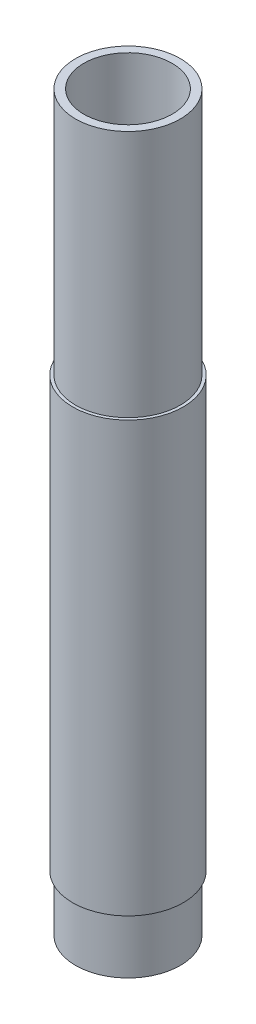
SolidWorks part; units mm, degrees
ref_plane "Front Plane" through (0, 0, 0) normal (0, 0, 1) x (1, 0, 0)
ref_plane "Top Plane" through (0, 0, 0) normal (0, 1, 0) x (1, 0, 0)
ref_plane "Right Plane" through (0, 0, 0) normal (1, 0, 0) x (0, 0, -1)
sketch "Sketch1" plane through (0, 0, 0) normal (0, 1, 0) x (1, 0, 0)
  circle A0 centre (0, 0) radius 15
  dimension "D1" = 30
extrude "Boss-Extrude1" add sketch "Sketch1" along normal blind 155
sketch "Sketch2" plane through (0, 155, 0) normal (0, 1, 0) x (1, 0, 0)
  circle A0 centre (0, 0) radius 15.85
  dimension "D1" = 31.7
extrude "Boss-Extrude2" add sketch "Sketch2" against normal blind 123 from offset 16 offset against normal yes
sketch "Sketch3" plane through (0, 155, 0) normal (0, 1, 0) x (1, 0, 0)
  circle A0 centre (0, 0) radius 15
extrude "Boss-Extrude3" add sketch "Sketch3" along normal blind 55
sketch "Sketch6" plane through (0, 0, 0) normal (0, -1, 0) x (1, 0, 0)
  circle A0 centre (0, 0) radius 12.65
  dimension "D1" = 25.3
extrude "Cut-Extrude2" cut sketch "Sketch6" against normal through all
